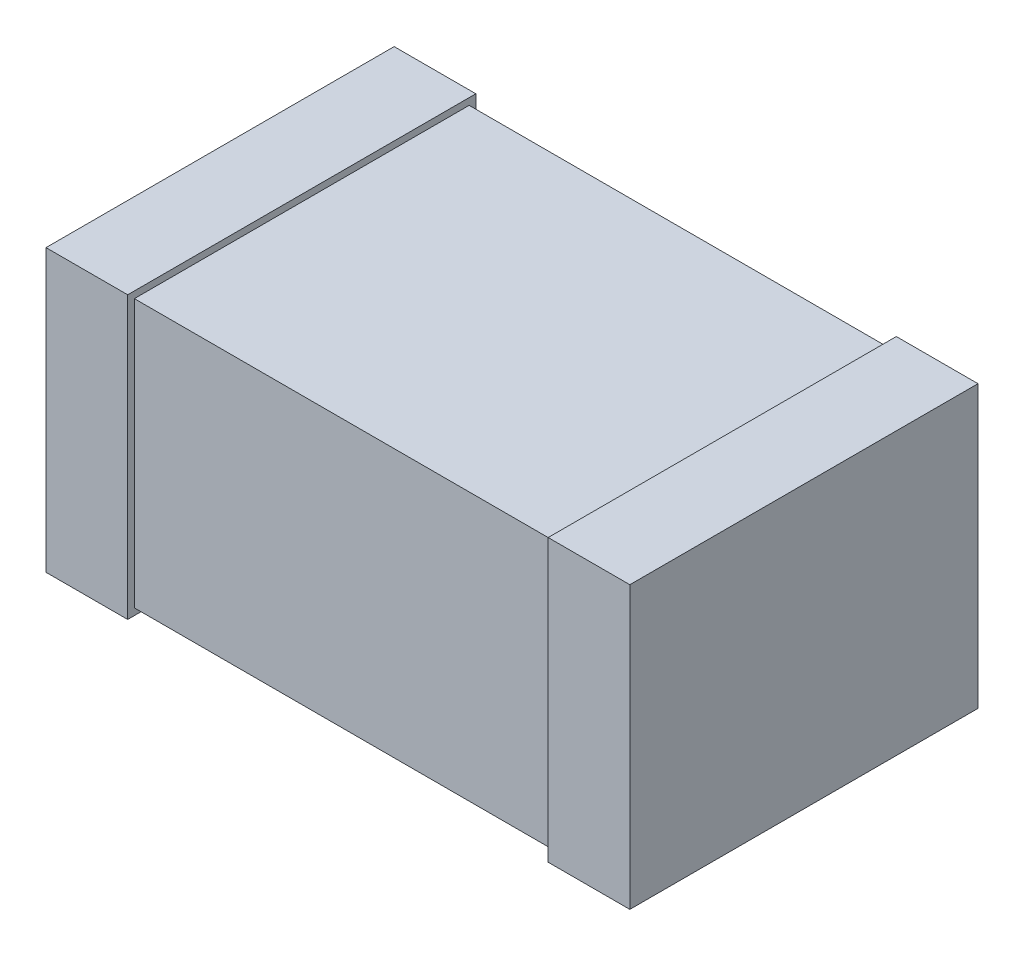
SolidWorks part; units mm, degrees
ref_plane "Front" through (0, 0, 0) normal (0, 0, 1) x (1, 0, 0)
ref_plane "Top" through (0, 0, 0) normal (0, 1, 0) x (1, 0, 0)
ref_plane "Right" through (0, 0, 0) normal (1, 0, 0) x (0, 0, -1)
sketch "Sketch1" plane through (0, 0, 0) normal (0, 1, 0) x (1, 0, 0)
  line L0 (-1.6, -1.25) -> (1.6, 1.25) construction
  line L1 (-1.6, 1.25) -> (1.6, 1.25)
  line L2 (-1.6, 1.25) -> (-1.6, -1.25)
  line L3 (-1.6, -1.25) -> (1.6, -1.25)
  line L4 (1.6, 1.25) -> (1.6, -1.25)
  dimension "D1" = 3.2
  dimension "D2" = 2.5
extrude "Boss-Extrude1" add sketch "Sketch1" along normal blind 2
sketch "Sketch2" plane through (1.6, 0, 0) normal (1, 0, 0) x (0, 0, -1)
  line L4 (-1.3, -0.05) -> (1.3, -0.05)
  line L5 (1.3, -0.05) -> (1.3, 2.05)
  line L6 (1.3, 2.05) -> (-1.3, 2.05)
  line L7 (-1.3, 2.05) -> (-1.3, -0.05)
  line L8 (-1.25, 0) -> (1.25, 0)
  line L9 (1.25, 0) -> (1.25, 2)
  line L10 (1.25, 2) -> (-1.25, 2)
  line L11 (-1.25, 2) -> (-1.25, 0)
  line L12 (-1.25, 0) -> (1.25, 0) construction
  line L13 (1.25, 0) -> (1.25, 2) construction
  line L14 (1.25, 2) -> (-1.25, 2) construction
  line L15 (-1.25, 2) -> (-1.25, 0) construction
  dimension "D1" = 0
  dimension "D2" = 0.05
extrude "Boss-Extrude2" add sketch "Sketch2" along normal blind 0.58 and the other way blind 0.03
mirror "Mirror1" about plane through (0, 0, 0) normal (1, 0, 0) of "Boss-Extrude2"
